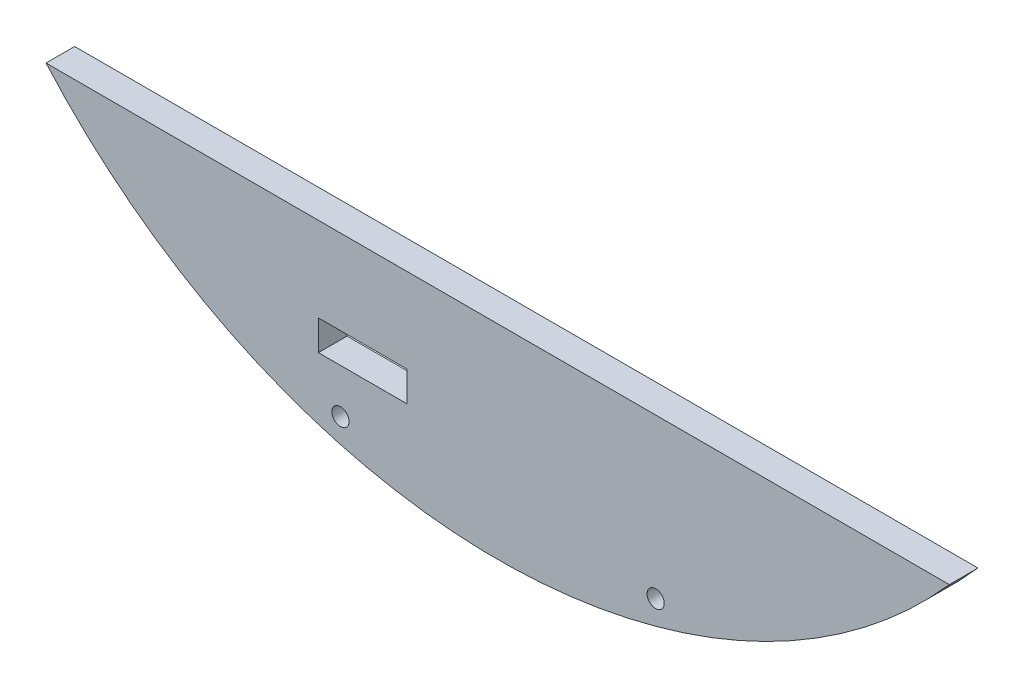
SolidWorks part; units mm, degrees
ref_plane "Plan de face" through (0, 0, 0) normal (0, 0, 1) x (1, 0, 0)
ref_plane "Plan de dessus" through (0, 0, 0) normal (0, 1, 0) x (1, 0, 0)
ref_plane "Plan de droite" through (0, 0, 0) normal (1, 0, 0) x (0, 0, -1)
sketch "Esquisse1" plane through (0, 0, 0) normal (0, 0, 1) x (1, 0, 0)
  line L0 (78.9656, -69.5576) -> (-78.6558, -69.5576)
  line L2 (-15.6266, -89.5576) -> (-31.1266, -89.5576)
  line L3 (-15.6266, -89.5576) -> (-15.6266, -84.3076)
  line L4 (-15.6266, -84.3076) -> (-31.1266, -84.3076)
  line L5 (-31.1266, -89.5576) -> (-31.1266, -84.3076)
  arc A1 (-78.6558, -69.5576) -> (78.9656, -69.5576) centre (0.1549, -0.1756) ccw
extrude "Boss.-Extru.1" add sketch "Esquisse1" along normal blind 5
sketch "Esquisse2" plane through (0, 0, 5) normal (0, 0, 1) x (1, 0, 0)
  circle A0 centre (-27.2792, -97.3076) radius 1.5
  circle A1 centre (27.7208, -97.3076) radius 1.5
extrude "Enlèv. mat.-Extru.1" cut sketch "Esquisse2" against normal blind 5
